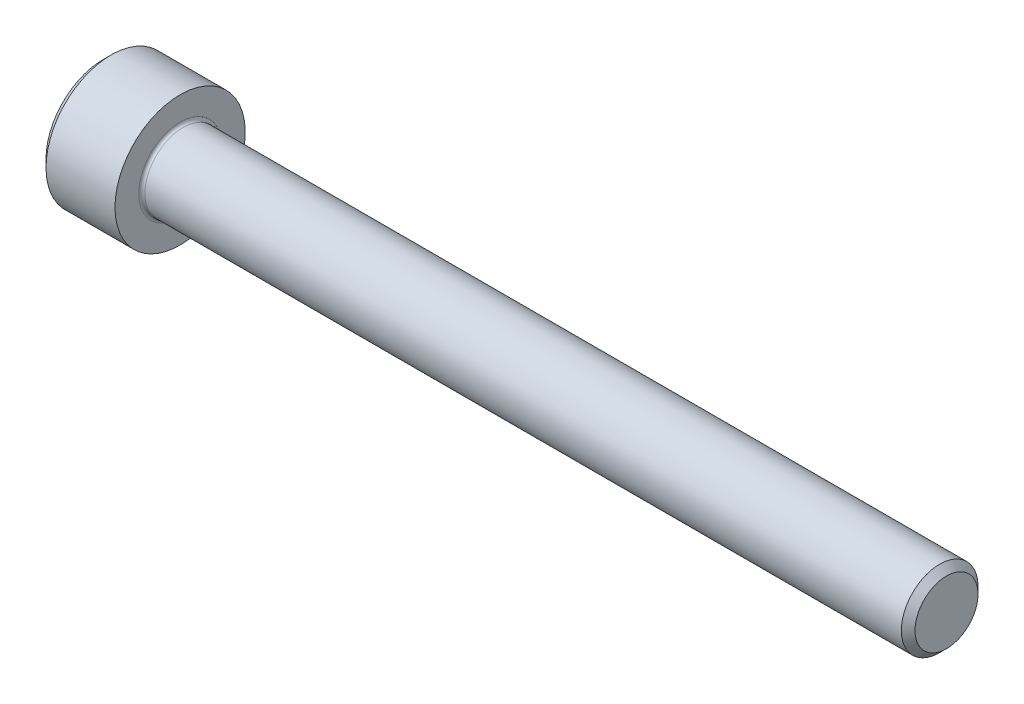
SolidWorks part; units mm, degrees
revolve "Base-Revolve" add sketch "BodySke"
sketch "BodySke" plane through (0, 0, 0) normal (0, 0, 1) x (1, 0, 0)
  line L0 (0, 0) -> (0, 3.75)
  line L1 (0.5, 4.25) -> (5, 4.25)
  line L2 (5, 4.25) -> (5, 2.5)
  line L3 (5, 2.5) -> (54.555, 2.5)
  line L4 (55, 2.055) -> (55, 0)
  line L5 (55, 0) -> (0, 0)
  line L6 (-31.75, 0) -> (127, 0) construction
  line L7 (0, 3.75) -> (0.5, 4.25)
  line L8 (55, 2.055) -> (54.555, 2.5)
  line L9 (0, -3.75) -> (0.5, -4.25) construction
  line L10 (55, -2.055) -> (54.555, -2.5) construction
  line L11 (5.8, 1.228) -> (5.8, -5.122) construction
  line L12 (33, 1.228) -> (33, -5.122) construction
  line L13 (5, 1.228) -> (5, -5.122) construction
  dimension "Diameter" = 5
  dimension "Head_ht" = 5
  dimension "Length" = 50
  dimension "Body_ch_ang" = 45
  dimension "Head_dia" = 8.5
  dimension "Head_ch_ang" = 45
  dimension "Minor_dia" = 4.11
  dimension "Advance" = 0.8
  dimension "Thread_nom" = 22
  dimension "Thread_length" = 50
  dimension "Head_ch_ht" = 0.5
cosmetic thread "ThreadCosmetic" [suppressed]
fillet "Fillet1" radius 0.2 1 edges at (5, 0, 2.5)
material "AISI 1020"
ref_plane "Plane1" through (0, 0, 0) normal (0, 0, 1) x (1, 0, 0)
ref_plane "Plane2" through (0, 0, 0) normal (0, 1, 0) x (1, 0, 0)
ref_plane "Plane3" through (0, 0, 0) normal (1, 0, 0) x (0, 0, -1)
other "Configuration Table"
sketch "Sketch2" plane through (0, 0, 0) normal (0, 0, 1) x (1, 0, 0)
  line L0 (0, 2.042) -> (2.5, 2.042)
  line L1 (2.5, 2.042) -> (3.6789, 0)
  line L2 (-31.75, 0) -> (127, 0) construction
  line L3 (3.6789, 0) -> (0, 0)
  line L4 (0, 0) -> (0, 2.042)
  line L5 (0, 3.75) -> (0, -3.75) construction
  line L6 (0, 0) -> (47.625, 0) construction
  line L7 (5, -4.25) -> (5, 4.25) construction
  dimension "D1" = 2.042
  dimension "D2" = 60
revolve "Hex-PreBroach" cut sketch "Sketch2" angle 360 about L6
sketch "Sketch3" plane through (0, 0, 0) normal (-1, 0, 0) x (0, 0.5, 0.866)
  line L0 (1.1789, 2.042) -> (-1.1789, 2.042)
  line L1 (-1.1789, 2.042) -> (-2.3579, 0)
  line L2 (1.1789, 2.042) -> (2.3579, 0)
  line L3 (1.1789, -2.042) -> (2.3579, 0)
  line L4 (1.1789, -2.042) -> (-1.1789, -2.042)
  line L5 (-1.1789, -2.042) -> (-2.3579, 0)
  dimension "D1" = 2.042
  dimension "D2" = 2.042
  dimension "Hex_size" = 4.084
extrude "Hex" cut sketch "Sketch3" against normal blind 2.5
sketch "Sketch4" plane through (0, 0, 0) normal (-1, 0, 0) x (0, 0, 1)
  line L0 (0, 0) -> (2.3876, 0)
  line L1 (0, 0) -> (6.1484, 3.5498) construction
  line L2 (0, 0) -> (1.1938, 2.0677)
  line L3 (1.9883, 0.576) -> (2.2704, 0.7389)
  line L4 (1.493, 1.4339) -> (1.7751, 1.5968)
  arc A0 (1.9883, 0.576) -> (1.493, 1.4339) centre (0, 0) ccw
  arc A1 (2.3876, 0) -> (2.2704, 0.7389) centre (0, 0) ccw
  arc A2 (1.1938, 2.0677) -> (1.7751, 1.5968) centre (0, 0) cw
  dimension "D1" = 30
  dimension "D2" = 60
  dimension "Spline_p_dim" = 0.9906
  dimension "D3" = 0.4953
extrude "Spline" [suppressed] cut sketch "Sketch4" against normal blind 2.5
pattern_circular "CirPattern1" [suppressed] count 6 every 60
sketch "Sketch5" plane through (0, 0, 0) normal (0, 0, 1) x (1, 0, 0)
  line L0 (-31.75, 0) -> (127, 0) construction
  line L2 (0, 3.75) -> (0, -3.75) construction
  circle A0 centre (2, 0) radius 0.675
  dimension "Drilled_hole_dia" = 1.35
  dimension "Drilled_hole_loc" = 2
extrude "Hole" [suppressed] cut sketch "Sketch5" against normal through all and the other way through all
pattern_circular "Drilled-4" [suppressed] count 2 every 60
pattern_circular "Drilled-6" [suppressed] count 3 every 60
sketch "ThdSchSke" plane through (0, 0, 0) normal (0, 0, 1) x (1, 0, 0)
  line L0 (33, -2.055) -> (32.6884, -2.5)
  line L1 (33, -2.055) -> (33.3116, -2.5)
  line L2 (33.3116, -2.5) -> (33.3116, -3.125)
  line L3 (-3.175, 0) -> (5.1513, 0) construction
  line L5 (33.3116, -3.125) -> (32.6884, -3.125)
  line L6 (32.6884, -3.125) -> (32.6884, -2.5)
  line L7 (0, 3.75) -> (0, -3.75) construction
  dimension "Thread_minor" = 4.11
  dimension "Diameter" = 5
  dimension "Start" = 33
revolve "ThreadSchematic" [suppressed] cut sketch "ThdSchSke" angle 360 about L3
pattern_linear "ThdSchPat" [suppressed]
equation "\"D2@Sketch3\" = \"Hex_size@Sketch3\" / 2"
equation "\"D1@Sketch3\" = \"Hex_size@Sketch3\" / 2"
equation "\"D1@Sketch2\" = \"Hex_size@Sketch3\" / 2"
equation "\"D3@Sketch4\" = \"Spline_p_dim@Sketch4\" / 2"
equation "\"Thread_minor@ThreadCosmetic\"  =  \"Minor_dia@BodySke\""
equation "\"D2@CirPattern1\" = 360 / \"Num_teeth@CirPattern1\""
equation "\"Wall_thickness@Sketch2\" = \"Head_ht@BodySke\" - \"Key_eng@Hex\""
equation "\"Thread_length@ThreadCosmetic\" = ((sgn( (\"Length@BodySke\" - \"Advance@BodySke\" ) - \"Thread_nom@BodySke\" )-1)*( (\"Length@BodySke\" - \"Advance@BodySke\" ) - \"Thread_nom@BodySke\" ))/-2+ \"Thread_nom@BodySke\""
equation "\"Thread_minor@ThdSchSke\" = \"Minor_dia@BodySke\""
equation "\"Diameter@ThdSchSke\" = \"Diameter@BodySke\""
equation "\"Overcut@ThdSchSke\" = \"Diameter@BodySke\" * 1.25"
equation "\"Start@ThdSchSke\" = \"Head_ht@BodySke\" + \"Length@BodySke\" - \"Thread_length@ThreadCosmetic\"  '---Non-countersunk---"
equation "\"Num_threads@ThdSchPat\" = int( \"Thread_length@ThreadCosmetic\" / \"Advance@BodySke\" + 0.999 )  + 1"
equation "\"Advance@ThdSchPat\" = \"Thread_length@ThreadCosmetic\" /  (\"Num_threads@ThdSchPat\" - 1) 'relax it"
equation "\"Num_threads@ThdSchPat\" = \"Num_threads@ThdSchPat\" - sgn( \"Num_threads@ThdSchPat\" - 1) '---chamfered tips only---"
